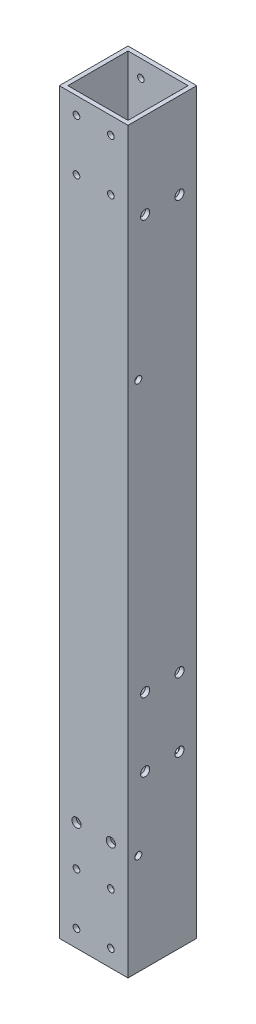
SolidWorks part; units mm, degrees
ref_plane "Front Plane" through (0, 0, 0) normal (0, 0, 1) x (1, 0, 0)
ref_plane "Top Plane" through (0, 0, 0) normal (0, 1, 0) x (1, 0, 0)
ref_plane "Right Plane" through (0, 0, 0) normal (1, 0, 0) x (0, 0, -1)
sketch "Sketch1" plane through (0, 0, 0) normal (0, 1, 0) x (1, 0, 0)
  line L0 (47.625, 3.175) -> (47.625, 47.625)
  line L1 (0, 0) -> (50.8, 0)
  line L2 (0, 0) -> (0, 50.8)
  line L3 (0, 50.8) -> (50.8, 50.8)
  line L4 (50.8, 0) -> (50.8, 50.8)
  line L5 (3.175, 47.625) -> (47.625, 47.625)
  line L6 (3.175, 3.175) -> (3.175, 47.625)
  line L7 (3.175, 3.175) -> (47.625, 3.175)
  dimension "D1" = 50.8
  dimension "D2" = 50.8
  dimension "D3" = 3.175
extrude "Boss-Extrude1" add sketch "Sketch1" along normal blind 546.1
sketch "Sketch2" plane through (0, 0, 0) normal (0, 0, 1) x (1, 0, 0)
  circle A0 centre (38.1, 12.7) radius 2.4638
  circle A1 centre (12.7, 12.7) radius 2.4638
  circle A2 centre (12.7, 50.8) radius 2.4638
  circle A3 centre (38.1, 50.8) radius 2.4638
  circle A4 centre (38.1, 495.3) radius 2.4638
  circle A5 centre (12.7, 495.3) radius 2.4638
  circle A6 centre (12.7, 533.4) radius 2.4638
  circle A7 centre (38.1, 533.4) radius 2.4638
extrude "Cut-Extrude1" cut sketch "Sketch2" against normal up to next
sketch "Sketch3" plane through (0, 0, -50.8) normal (0, 0, -1) x (-1, 0, 0)
  circle A0 centre (-38.1, 533.4) radius 2.4638
  circle A1 centre (-12.7, 533.4) radius 2.4638
  circle A2 centre (-38.1, 429.26) radius 2.4638
  circle A3 centre (-12.7, 429.26) radius 2.4638
  circle A4 centre (-38.1, 325.12) radius 2.4638
  circle A5 centre (-12.7, 325.12) radius 2.4638
  circle A6 centre (-38.1, 220.98) radius 2.4638
  circle A7 centre (-12.7, 220.98) radius 2.4638
  circle A8 centre (-38.1, 116.84) radius 2.4638
  circle A9 centre (-12.7, 116.84) radius 2.4638
  circle A10 centre (-38.1, 12.7) radius 2.4638
  circle A11 centre (-12.7, 12.7) radius 2.4638
extrude "Cut-Extrude2" cut sketch "Sketch3" against normal up to next
hole_wizard "1/4 (0.25) Diameter Hole1" positions "Sketch4" profile "Sketch5" hole size "1/4" standard "ANSI Inch" end condition through all
sketch "Sketch4" plane through (50.8, 0, 0) normal (1, 0, 0) x (0, 0, -1)
  point P0 (12.7, 482.6)
  point P3 (38.1, 482.6)
sketch "Sketch5" plane through (50.8, 482.6, -12.7) normal (0, 1, 0) x (0, 0, -1)
  line L0 (0, 0) -> (0, 50.8)
  line L1 (0, 50.8) -> (3.3734, 50.8)
  line L2 (3.3734, 50.8) -> (3.3734, 0)
  line L5 (3.3734, 0) -> (0, 0)
  line L11 (0, -6.35) -> (0, 107.95) construction
  dimension "Thru Hole Dia." = 6.7469
  dimension "Thru Hole Depth" = 50.8
sketch "Sketch10" plane through (0, 0, 0) normal (-1, 0, 0) x (0, 0, 1)
  circle A0 centre (-7.62, 356.2414) radius 2.5798
  circle A1 centre (-7.62, 221.6573) radius 2.6157
extrude "Cut-Extrude3" cut sketch "Sketch10" against normal up to next
ref_plane "Plane1" through (457.2, 622.3, -16.51) normal (0, 1, 0) x (1, 0, 0)
sketch "Sketch12" plane through (0, 0, 0) normal (-1, 0, 0) x (0, 0, 1)
  circle A0 centre (-12.7, 176.7025) radius 3.3734
  circle A1 centre (-12.7, 125.9025) radius 3.3734
  circle A2 centre (-38.1, 125.9025) radius 3.3734
  circle A3 centre (-38.1, 176.7025) radius 3.3734
  dimension "D1" = 6.7469
extrude "Cut-Extrude4" cut sketch "Sketch12" against normal through all
sketch "Sketch13" plane through (50.8, 0, 0) normal (1, 0, 0) x (0, 0, -1)
  circle A0 centre (7.62, 379.321) radius 2.5797
  circle A1 centre (7.62, 74.521) radius 2.5797
extrude "Cut-Extrude5" cut sketch "Sketch13" against normal up to next
sketch "Sketch14" plane through (0, 0, 0) normal (0, 0, 1) x (1, 0, 0)
  circle A0 centre (12.7, 80.518) radius 3.3734
  circle A1 centre (38.1, 80.518) radius 3.3734
extrude "Cut-Extrude6" cut sketch "Sketch14" against normal through all
sketch "Sketch15" plane through (0, 0, -50.8) normal (0, 0, -1) x (-1, 0, 0)
  circle A0 centre (-38.1, 80.518) radius 6.35
  circle A1 centre (-12.7, 80.518) radius 6.35
  dimension "D1" = 12.7
  dimension "D2" = 12.7
extrude "Cut-Extrude7" cut sketch "Sketch15" against normal up to next
